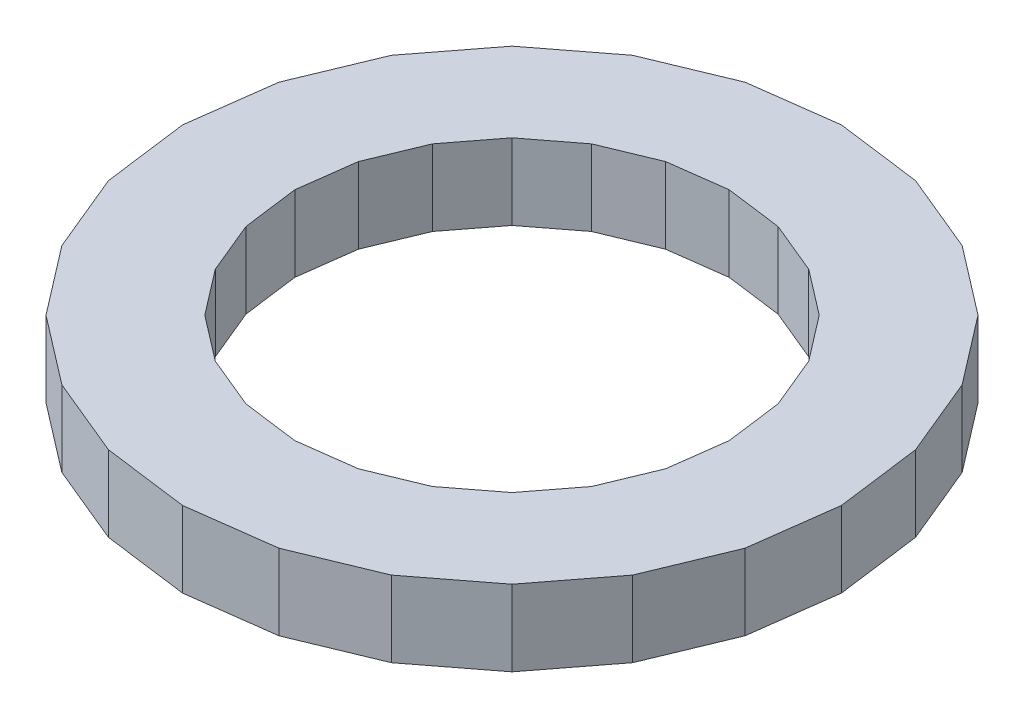
SolidWorks part; units mm, degrees
ref_plane "Front Plane" through (0, 0, 0) normal (0, 0, 1) x (1, 0, 0)
ref_plane "Top Plane" through (0, 0, 0) normal (0, 1, 0) x (1, 0, 0)
ref_plane "Right Plane" through (0, 0, 0) normal (1, 0, 0) x (0, 0, -1)
sketch "Sketch3" plane through (0, 0, 0) normal (0, 1, 0) x (1, 0, 0)
  line L0 (0, 0) -> (-54.5226, 0) construction
  line L1 (-82.7037, 0) -> (-79.8856, -21.4053)
  line L2 (-79.8856, -21.4053) -> (-71.6235, -41.3519)
  line L3 (-71.6235, -41.3519) -> (-58.4804, -58.4804)
  line L4 (-58.4804, -58.4804) -> (-41.3519, -71.6235)
  line L5 (-41.3519, -71.6235) -> (-21.4053, -79.8856)
  line L6 (-21.4053, -79.8856) -> (0, -82.7037)
  line L7 (0, -82.7037) -> (21.4053, -79.8856)
  line L8 (21.4053, -79.8856) -> (41.3519, -71.6235)
  line L9 (41.3519, -71.6235) -> (58.4804, -58.4804)
  line L10 (58.4804, -58.4804) -> (71.6235, -41.3519)
  line L11 (71.6235, -41.3519) -> (79.8856, -21.4053)
  line L12 (79.8856, -21.4053) -> (82.7037, 0)
  line L13 (82.7037, 0) -> (79.8856, 21.4053)
  line L14 (79.8856, 21.4053) -> (71.6235, 41.3519)
  line L15 (71.6235, 41.3519) -> (58.4804, 58.4804)
  line L16 (58.4804, 58.4804) -> (41.3519, 71.6235)
  line L17 (41.3519, 71.6235) -> (21.4053, 79.8856)
  line L18 (21.4053, 79.8856) -> (0, 82.7037)
  line L19 (0, 82.7037) -> (-21.4053, 79.8856)
  line L20 (-21.4053, 79.8856) -> (-41.3519, 71.6235)
  line L21 (-41.3519, 71.6235) -> (-58.4804, 58.4804)
  line L22 (-58.4804, 58.4804) -> (-71.6235, 41.3519)
  line L23 (-71.6235, 41.3519) -> (-79.8856, 21.4053)
  line L24 (-79.8856, 21.4053) -> (-82.7037, 0)
  line L25 (-54.5226, 0) -> (-52.6648, -14.1115)
  line L26 (-52.6648, -14.1115) -> (-47.218, -27.2613)
  line L27 (-47.218, -27.2613) -> (-38.5533, -38.5533)
  line L28 (-38.5533, -38.5533) -> (-27.2613, -47.218)
  line L29 (-27.2613, -47.218) -> (-14.1115, -52.6648)
  line L30 (-14.1115, -52.6648) -> (0, -54.5226)
  line L31 (0, -54.5226) -> (14.1115, -52.6648)
  line L32 (14.1115, -52.6648) -> (27.2613, -47.218)
  line L33 (27.2613, -47.218) -> (38.5533, -38.5533)
  line L34 (38.5533, -38.5533) -> (47.218, -27.2613)
  line L35 (47.218, -27.2613) -> (52.6648, -14.1115)
  line L36 (52.6648, -14.1115) -> (54.5226, 0)
  line L37 (54.5226, 0) -> (52.6648, 14.1115)
  line L38 (52.6648, 14.1115) -> (47.218, 27.2613)
  line L39 (47.218, 27.2613) -> (38.5533, 38.5533)
  line L40 (38.5533, 38.5533) -> (27.2613, 47.218)
  line L41 (27.2613, 47.218) -> (14.1115, 52.6648)
  line L42 (14.1115, 52.6648) -> (0, 54.5226)
  line L43 (0, 54.5226) -> (-14.1115, 52.6648)
  line L44 (-14.1115, 52.6648) -> (-27.2613, 47.218)
  line L45 (-27.2613, 47.218) -> (-38.5533, 38.5533)
  line L46 (-38.5533, 38.5533) -> (-47.218, 27.2613)
  line L47 (-47.218, 27.2613) -> (-52.6648, 14.1115)
  line L48 (-52.6648, 14.1115) -> (-54.5226, 0)
  line L49 (-82.7037, 0) -> (-54.5226, 0) construction
  circle A0 centre (0, 0) radius 81.9962 construction
  circle A1 centre (0, 0) radius 54.0562 construction
  dimension "D1" = 21.59
  dimension "D2" = 27.94
extrude "Boss-Extrude3" add sketch "Sketch3" along normal blind 19.05
